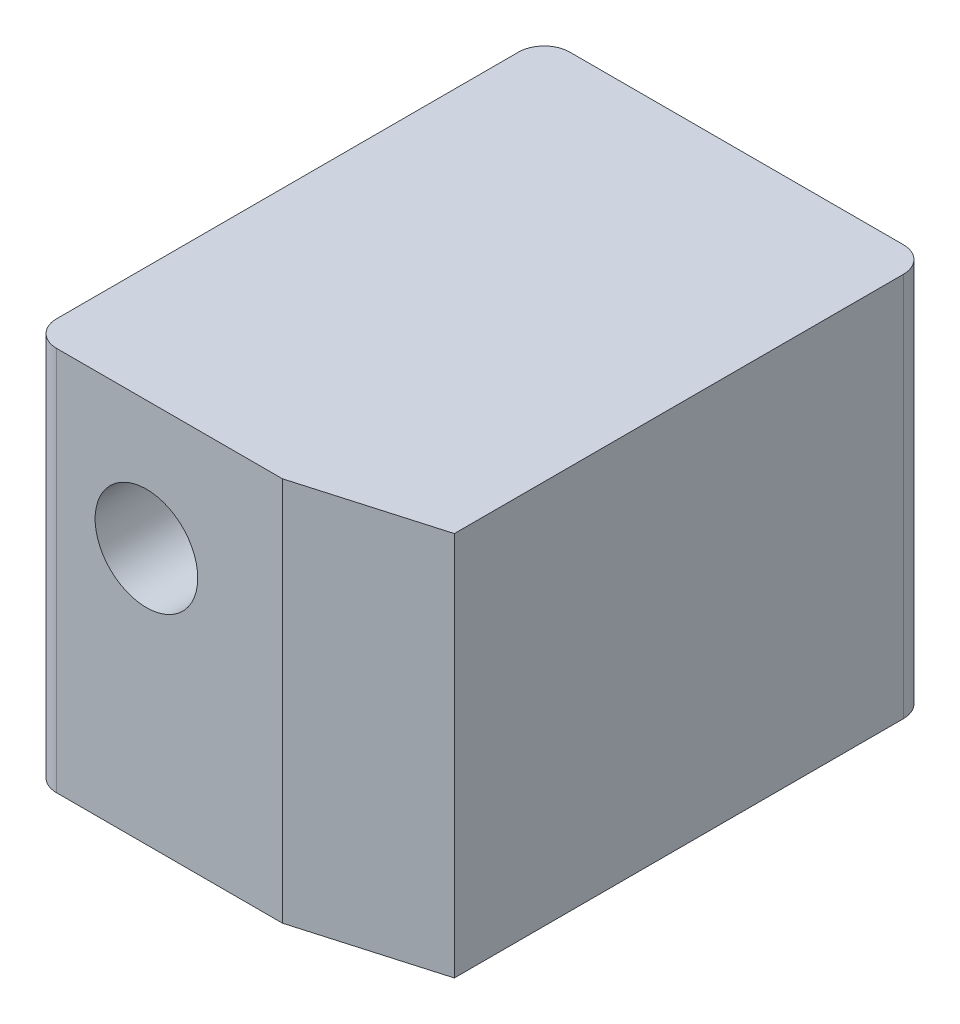
SolidWorks part; units mm, degrees
ref_plane "Plan de face" through (0, 0, 0) normal (0, 0, 1) x (1, 0, 0)
ref_plane "Plan de dessus" through (0, 0, 0) normal (0, 1, 0) x (1, 0, 0)
ref_plane "Plan de droite" through (0, 0, 0) normal (1, 0, 0) x (0, 0, -1)
sketch "Esquisse1" plane through (0, 0, 0) normal (0, 1, 0) x (1, 0, 0)
  line L0 (0, 0) -> (7.5, 0)
  line L1 (0, 0) -> (-7.5, 0)
  line L2 (-7.5, 0) -> (-7.5, 20)
  line L3 (-7.5, 20) -> (7.5, 20)
  line L4 (7.5, 20) -> (7.5, 0)
  dimension "D1" = 20
  dimension "D2" = 15
extrude "Boss.-Extru.1" add sketch "Esquisse1" along normal blind 15
sketch "Esquisse2" plane through (0, 0, 0) normal (0, -1, 0) x (1, 0, 0)
  line L0 (-7.5, -20) -> (-7.5, -16) construction
  line L1 (-7.5, -20) -> (-7.5, 0) construction
  line L2 (-7.5, -16) -> (1.5, -16) construction
  line L3 (7.5, 0) -> (7.5, -4) construction
  line L4 (7.5, 0) -> (7.5, -20) construction
  line L6 (7.5, -4) -> (-1.5, -4) construction
  circle A3 centre (-3, -16) radius 2
  circle A4 centre (3, -4) radius 2
  dimension "D2" = 9
  dimension "D1" = 4
  dimension "D3" = 4
  dimension "D4" = 9
extrude "Enlèv. mat.-Extru.1" cut sketch "Esquisse2" against normal blind 12
sketch "Esquisse3" plane through (0, 0, 0) normal (0, 0, 1) x (1, 0, 0)
  line L0 (0, 0) -> (-3, 0) construction
  line L1 (-7.5, 0) -> (7.5, 0) construction
  line L2 (-3, 0) -> (-3, 10) construction
  circle A1 centre (-3, 10) radius 2
  dimension "D1" = 10
  dimension "D2" = 3
extrude "Enlèv. mat.-Extru.2" cut sketch "Esquisse3" against normal blind 12
fillet "Congé1" radius 1 3 edges at (7.5, 7.5, -20) (-7.5, 7.5, -20) (-7.5, 7.5, 0)
sketch "Esquisse5" plane through (0, 15, 0) normal (0, 1, 0) x (1, 0, 0)
  line L0 (7.5, 0) -> (2.3, 0)
  line L1 (-6.5, 0) -> (7.5, 0) construction
  line L2 (7.5, 0) -> (7.5, 1.5)
  line L3 (2.3, 0) -> (7.5, 1.5)
extrude "Enlèv. mat.-Extru.3" cut sketch "Esquisse5" against normal up to next
